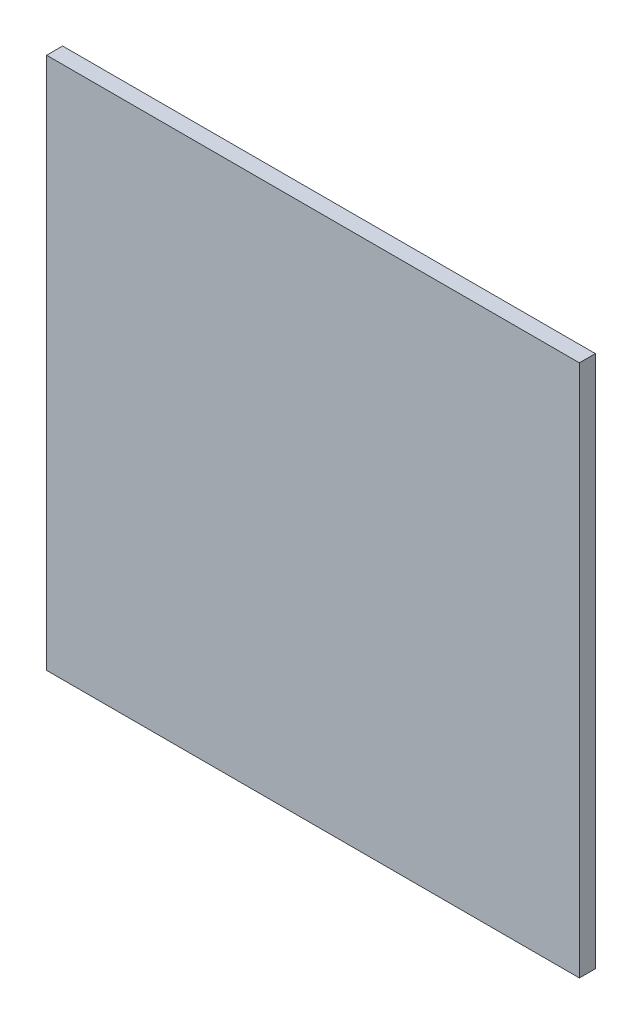
SolidWorks part; units mm, degrees
ref_plane "Plan de face" through (0, 0, 0) normal (0, 0, 1) x (1, 0, 0)
ref_plane "Plan de dessus" through (0, 0, 0) normal (0, 1, 0) x (1, 0, 0)
ref_plane "Plan de droite" through (0, 0, 0) normal (1, 0, 0) x (0, 0, -1)
sketch "Esquisse1" plane through (0, 0, 0) normal (0, 0, 1) x (1, 0, 0)
  line L1 (-50, -50) -> (50, -50)
  line L2 (-50, -50) -> (-50, 50)
  line L3 (-50, 50) -> (50, 50)
  line L4 (50, -50) -> (50, 50)
  line L5 (0, 50) -> (0, -50) construction
  line L6 (-50, 0) -> (50, 0) construction
  point P0 (0, 0)
  dimension "D1" = 100
  dimension "D2" = 100
extrude "Boss.-Extru.1" add sketch "Esquisse1" along normal blind 3
